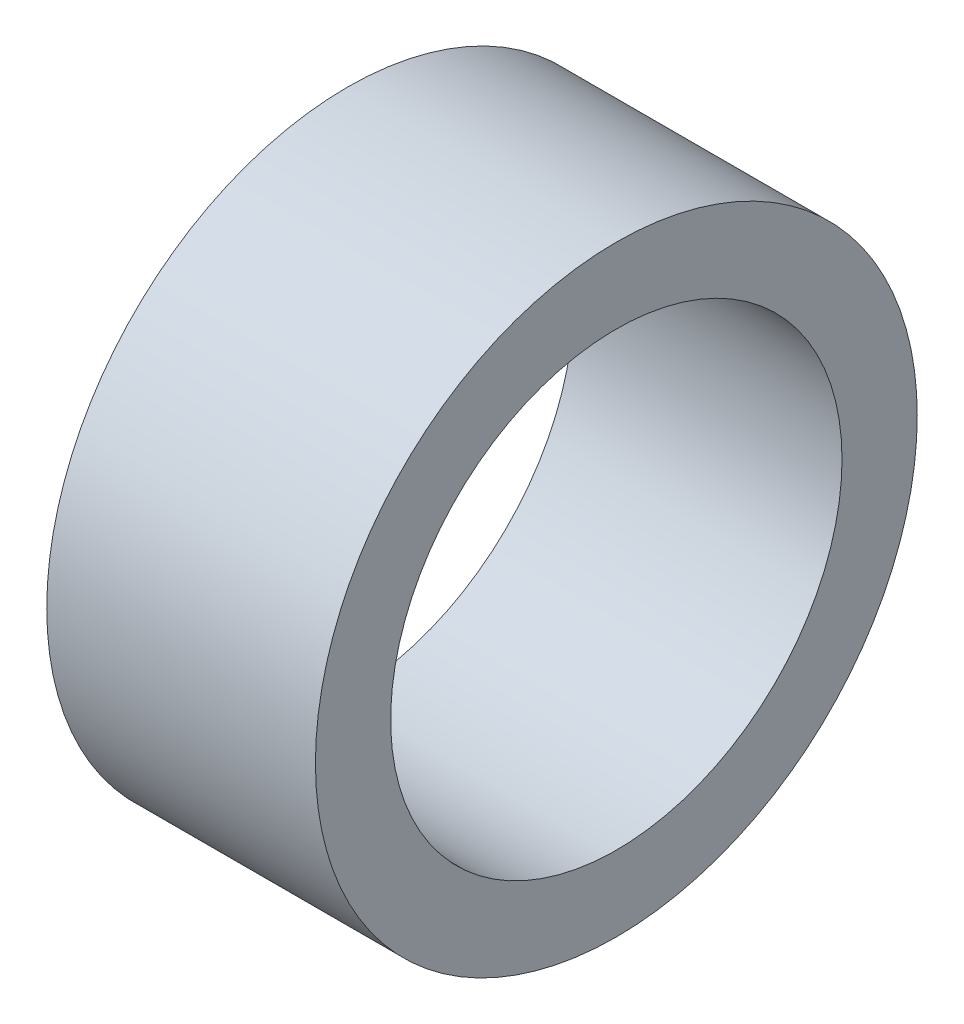
SolidWorks part; units mm, degrees
ref_plane "Plan de face" through (0, 0, 0) normal (0, 0, 1) x (1, 0, 0)
ref_plane "Plan de dessus" through (0, 0, 0) normal (0, 1, 0) x (1, 0, 0)
ref_plane "Plan de droite" through (0, 0, 0) normal (1, 0, 0) x (0, 0, -1)
sketch "Esquisse1" plane through (0, 0, 0) normal (1, 0, 0) x (0, 0, -1)
  circle A0 centre (0, 0) radius 2.8
  circle A1 centre (0, 0) radius 2.1
  dimension "D1" = 5.6
  dimension "D2" = 4.2
extrude "Boss.-Extru.1" add sketch "Esquisse1" along normal mid plane 2.5
